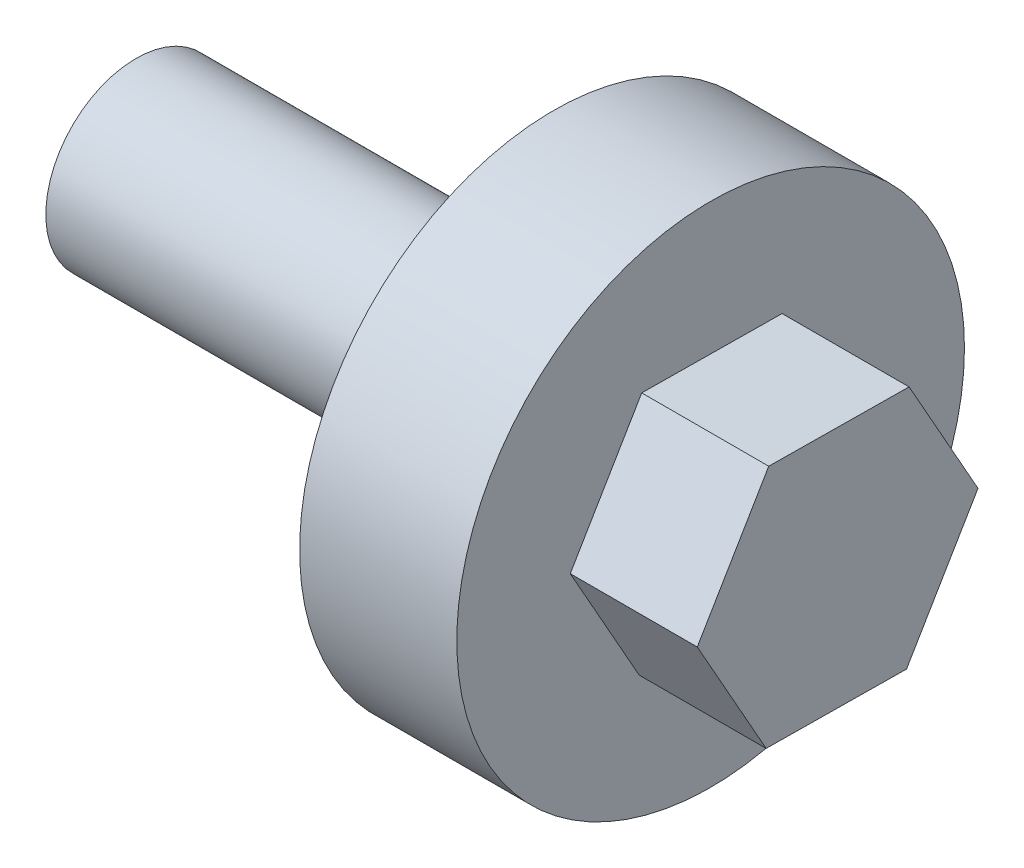
SolidWorks part; units mm, degrees
ref_plane "Front Plane" through (0, 0, 0) normal (0, 0, 1) x (1, 0, 0)
ref_plane "Top Plane" through (0, 0, 0) normal (0, 1, 0) x (1, 0, 0)
ref_plane "Right Plane" through (0, 0, 0) normal (1, 0, 0) x (0, 0, -1)
sketch "Sketch1" plane through (0, 0, 0) normal (1, 0, 0) x (0, 0, -1)
  circle A0 centre (-75.5297, 661.0492) radius 46.3344
  point P3 (-121.8641, 661.0492)
extrude "Boss-Extrude1" add sketch "Sketch1" along normal blind 28.6842
sketch "Sketch2" plane through (28.6842, 0, 0) normal (1, 0, 0) x (0, 0, -1)
  line L1 (-101.1504, 661.319) -> (-88.5737, 638.9959)
  line L2 (-88.5737, 638.9959) -> (-62.9529, 638.7262)
  line L3 (-62.9529, 638.7262) -> (-49.909, 660.7795)
  line L4 (-49.909, 660.7795) -> (-62.4857, 683.1025)
  line L5 (-62.4857, 683.1025) -> (-88.1064, 683.3723)
  line L6 (-88.1064, 683.3723) -> (-101.1504, 661.319)
  circle A0 centre (-75.5297, 661.0492) radius 22.1894 construction
extrude "Boss-Extrude2" add sketch "Sketch2" along normal blind 23.1826
sketch "Sketch3" plane through (0, 0, 0) normal (-1, 0, 0) x (0, 0, 1)
  circle A0 centre (75.5297, 661.0492) radius 16.4605
  point P3 (89.3374, 670.0101)
extrude "Boss-Extrude3" add sketch "Sketch3" along normal blind 76.2
